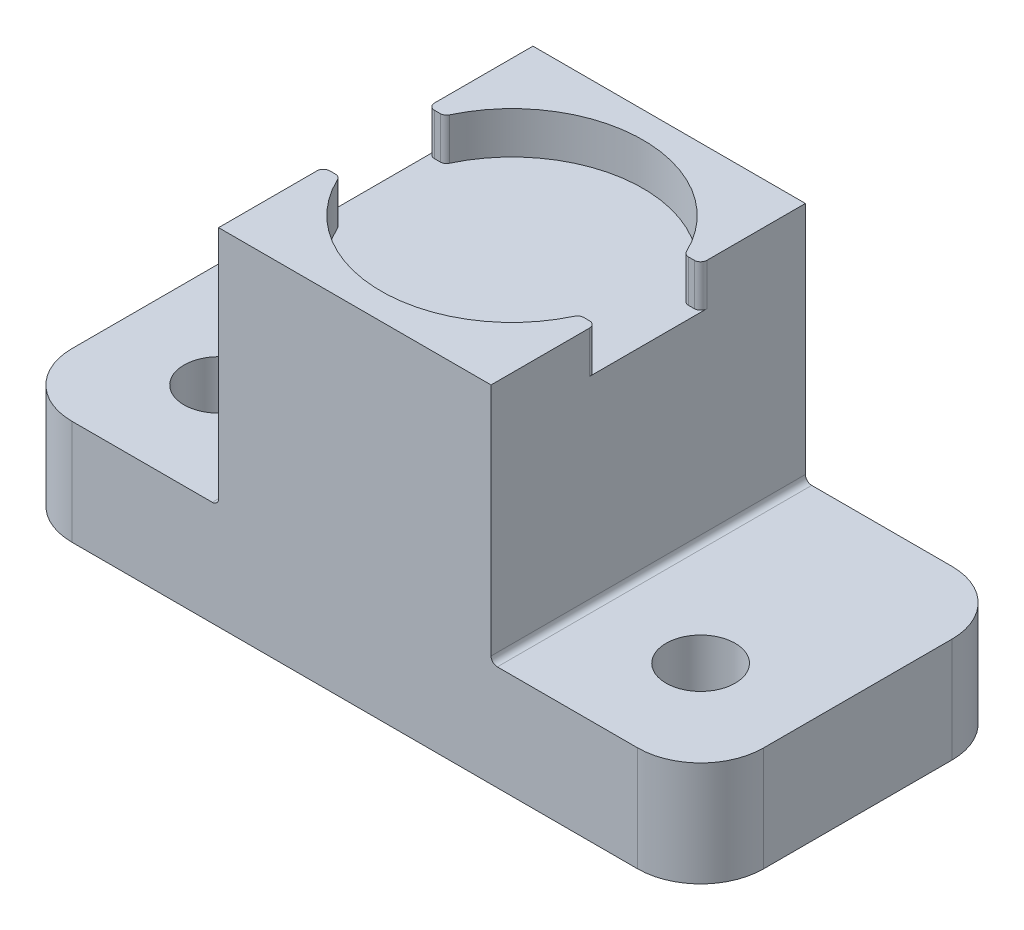
SolidWorks part; units mm, degrees
material "ﾎﾟﾘｴﾁﾚﾝｲﾐﾝ(PEI)"
ref_plane "正面" through (0, 0, 0) normal (0, 0, 1) x (1, 0, 0)
ref_plane "平面" through (0, 0, 0) normal (0, 1, 0) x (1, 0, 0)
ref_plane "右側面" through (0, 0, 0) normal (1, 0, 0) x (0, 0, -1)
sketch "ｽｹｯﾁ1" plane through (0, 0, 0) normal (0, 0, 1) x (1, 0, 0)
  line L0 (0, 0) -> (0, 8.25) construction
  line L1 (16.5, 2.5) -> (-16.5, 2.5)
  line L2 (16.5, 2.5) -> (16.5, -2.5)
  line L3 (16.5, -2.5) -> (-16.5, -2.5)
  line L4 (-16.5, 2.5) -> (-16.5, -2.5)
  line L5 (16.5, 2.5) -> (-16.5, -2.5) construction
  line L6 (16.5, -2.5) -> (-16.5, 2.5) construction
  line L8 (6.5, 14) -> (-6.5, 14)
  line L9 (6.5, 14) -> (6.5, 2.5)
  line L10 (6.5, 2.5) -> (-6.5, 2.5)
  line L11 (-6.5, 14) -> (-6.5, 2.5)
  line L12 (6.5, 14) -> (-6.5, 2.5) construction
  line L13 (6.5, 2.5) -> (-6.5, 14) construction
  point P0 (0, 0)
  dimension "D1" = 5
  dimension "D2" = 33
  dimension "D3" = 13
  dimension "D4" = 11.5
extrude "ﾎﾞｽ - 押し出し1" add sketch "ｽｹｯﾁ1" along normal blind 15 contours L1 L4 L3 L2 | L8 L11 L1 L9
sketch "ｽｹｯﾁ2" plane through (0, 2.5, 0) normal (0, 1, 0) x (1, 0, 0)
  line L0 (-6.5, -15) -> (-16.5, -15) construction
  line L2 (-16.5, -15) -> (-16.5, 0) construction
  line L3 (-6.5, -10) -> (-16.5, -10) construction
  line L4 (-6.5, -15) -> (-6.5, 0) construction
  line L5 (0, 0) -> (0, -15) construction
  line L6 (6.5, -15) -> (-6.5, -15) construction
  circle A0 centre (-11.5, -10) radius 1.65
  circle A1 centre (11.5, -10) radius 1.65
  dimension "D1" = 3.3
  dimension "D2" = 5
extrude "ｶｯﾄ - 押し出し1" cut sketch "ｽｹｯﾁ2" against normal through all
sketch "ｽｹｯﾁ3" plane through (0, 14, 0) normal (0, 1, 0) x (1, 0, 0)
  line L0 (0, 0) -> (0, -15) construction
  line L1 (6.5, 0) -> (-6.5, 0) construction
  line L2 (6.5, -15) -> (-6.5, -15) construction
  line L3 (-6.5, -15) -> (-6.5, 0) construction
  line L4 (6.5, -5) -> (-6.5, -5)
  line L5 (6.5, -5) -> (6.5, -10)
  line L6 (6.5, -10) -> (-6.5, -10)
  line L7 (-6.5, -5) -> (-6.5, -10)
  line L8 (6.5, -5) -> (-6.5, -10) construction
  line L9 (6.5, -10) -> (-6.5, -5) construction
  circle A0 centre (0, -7.5) radius 6.25
  line M4 (-6.5, 0) -> (-6.5, -15)
  line M6 (6.5, -15) -> (6.5, 0)
  dimension "D1" = 12.5
  dimension "D2" = 5
extrude "ｶｯﾄ - 押し出し3" cut sketch "ｽｹｯﾁ3" against normal blind 2 contours L4 A0 | L6 A0 | L6 A0 L4 | A0 L4 L6 M4 | A0 L6 L4 M6
fillet "ﾌｨﾚｯﾄ2" radius 0.3 8 edges at (6.5, 13, 5) (-5.7282, 13, 5) (5.7282, 13, 5) (6.5, 13, 10) (5.7282, 13, 10) (-5.7282, 13, 10) (-6.5, 13, 10) (-6.5, 13, 5)
fillet "ﾌｨﾚｯﾄ3" radius 0.3 2 edges at (6.5, 2.5, 7.5) (-6.5, 2.5, 7.5)
fillet "ﾌｨﾚｯﾄ4" radius 3 4 edges at (16.5, 0, 0) (16.5, 0, 15) (-16.5, 0, 0) (-16.5, 0, 15)
